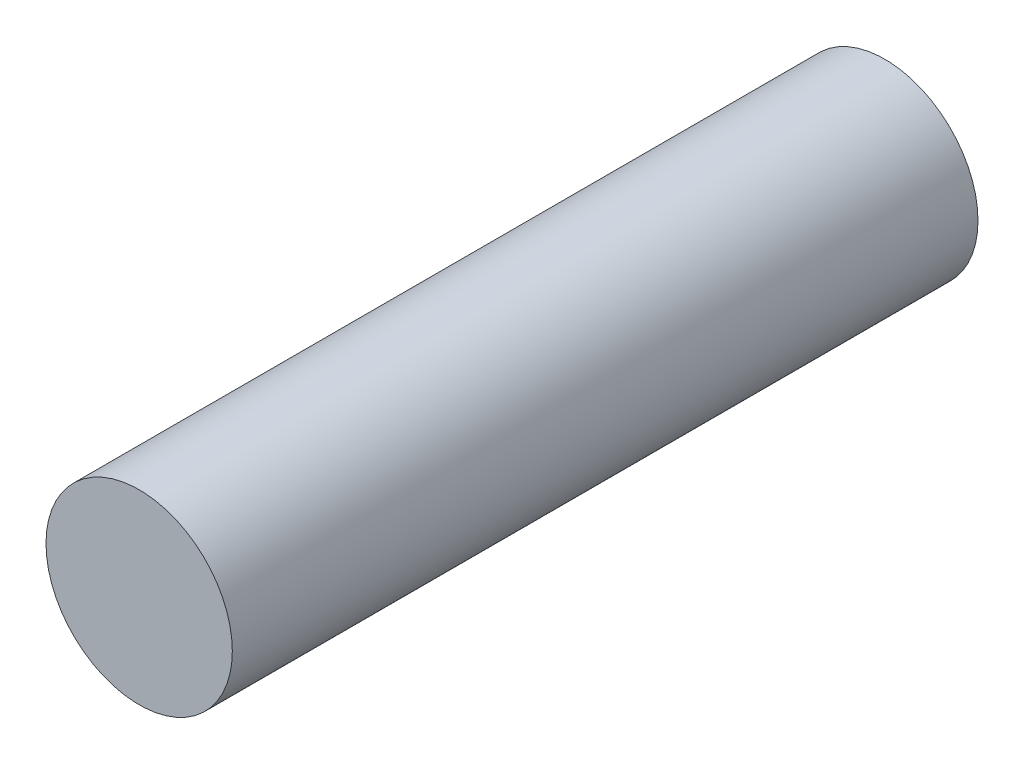
SolidWorks part; units mm, degrees
ref_plane "Ön Düzlem" through (0, 0, 0) normal (0, 0, 1) x (1, 0, 0)
ref_plane "Üst Düzlem" through (0, 0, 0) normal (0, 1, 0) x (1, 0, 0)
ref_plane "Sağ Düzlem" through (0, 0, 0) normal (1, 0, 0) x (0, 0, -1)
sketch "Çizim1" plane through (0, 0, 0) normal (0, 0, 1) x (1, 0, 0)
  circle A0 centre (0, 0) radius 4.76
  dimension "D1" = 9.52
extrude "Yükseklik-Ekstrüzyon1" add sketch "Çizim1" along normal blind 38.1
